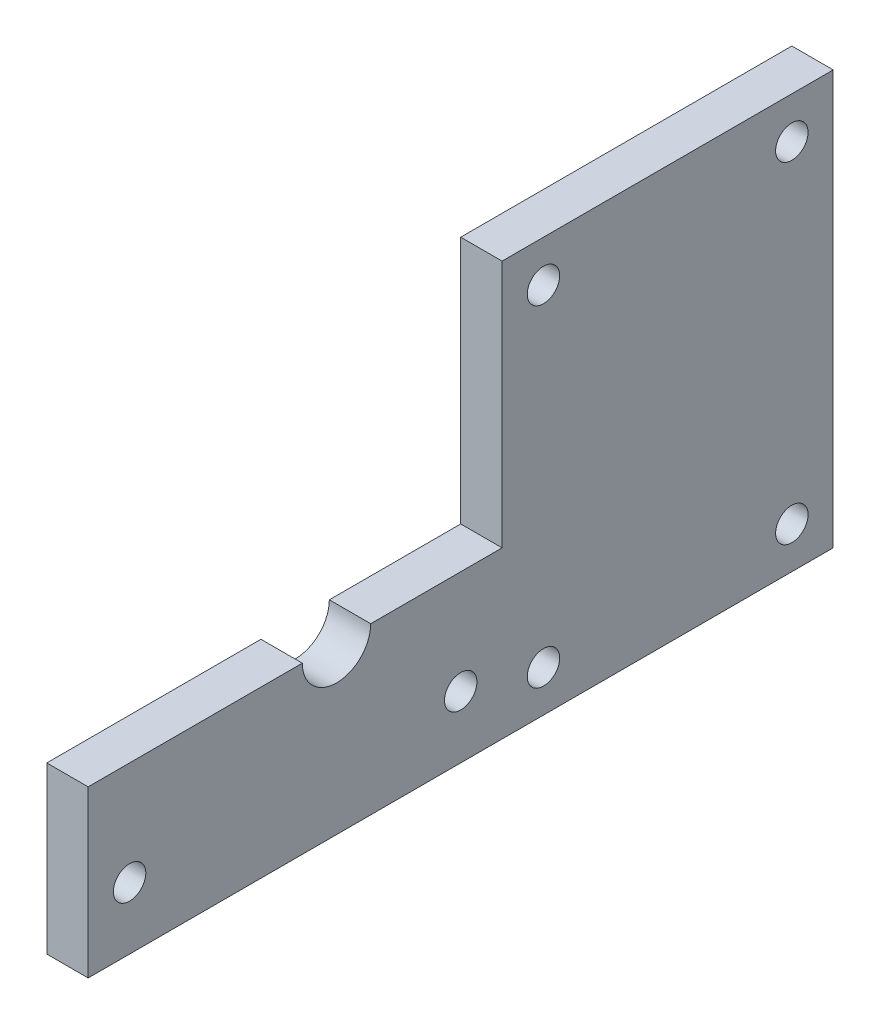
SolidWorks part; units mm, degrees
ref_plane "Front" through (0, 0, 0) normal (0, 0, 1) x (1, 0, 0)
ref_plane "Top" through (0, 0, 0) normal (0, 1, 0) x (1, 0, 0)
ref_plane "Right" through (0, 0, 0) normal (1, 0, 0) x (0, 0, -1)
sketch "Sketch1" plane through (0, 0, 0) normal (1, 0, 0) x (0, 0, -1)
  line L0 (-50.8, -6.35) -> (12.7, -6.35)
  line L1 (-50.8, -31.75) -> (63.5, -31.75)
  line L2 (-50.8, -31.75) -> (-50.8, -6.35)
  line L3 (12.7, 31.75) -> (63.5, 31.75)
  line L4 (63.5, -31.75) -> (63.5, 31.75)
  line L7 (12.7, -6.35) -> (12.7, 31.75)
  point P0 (0, 0)
  dimension "D1" = 25.4
  dimension "D2" = 50.8
  dimension "D3" = 63.5
  dimension "D4" = 31.75
  dimension "D5" = 63.5
  dimension "D6" = 63.5
extrude "Boss-Extrude1" add sketch "Sketch1" along normal blind 6.35
hole_wizard "#9 (0.196) Diameter Hole1" positions "Sketch3" profile "Sketch2" hole size "#9" standard "ANSI Inch"
sketch "Sketch3" plane through (0, 0, 0) normal (-1, 0, 0) x (0, 0, 1)
  line L0 (50.8, -31.75) -> (-63.5, -31.75) construction
  line L1 (50.8, -6.35) -> (50.8, -31.75) construction
  point P0 (44.45, -22.225)
  point P2 (-6.35, -22.225)
  dimension "D1" = 9.525
  dimension "D2" = 0
  dimension "D3" = 50.8
  dimension "D4" = 6.35
sketch "Sketch2" plane through (0, -22.225, 44.45) normal (0, 1, 0) x (0, 0, 1)
  line L0 (0, 0) -> (0, 71.5997)
  line L1 (0, 71.5997) -> (2.4892, 70.104)
  line L2 (2.4892, 70.104) -> (2.4892, 0)
  line L5 (2.4892, 0) -> (0, 0)
  line L10 (0, 71.5997) -> (-2.4892, 70.104) construction
  line L11 (0, -6.35) -> (0, 107.95) construction
  dimension "Hole Dia." = 4.9784
  dimension "Hole Depth" = 70.104
  dimension "Drill Angle" = 118
hole_wizard "#9 (0.196) Diameter Hole2" positions "Sketch5" profile "Sketch4" hole size "#9" standard "ANSI Inch"
sketch "Sketch5" plane through (0, 0, 0) normal (-1, 0, 0) x (0, 0, 1)
  line L0 (50.8, -31.75) -> (-63.5, -31.75) construction
  line L1 (-63.5, -31.75) -> (-63.5, 31.75) construction
  point P0 (-57.15, -25.4)
  point P2 (-19.05, -25.4)
  point P4 (-19.05, 25.4)
  point P6 (-57.15, 25.4)
  dimension "D1" = 6.35
  dimension "D2" = 6.35
  dimension "D3" = 0
  dimension "D4" = 50.8
  dimension "D5" = 38.1
  dimension "D6" = 50.8
  dimension "D7" = 38.1
  dimension "D8" = 0
sketch "Sketch4" plane through (0, -25.4, -57.15) normal (0, 1, 0) x (0, 0, 1)
  line L0 (0, 0) -> (0, 71.5997)
  line L1 (0, 71.5997) -> (2.4892, 70.104)
  line L2 (2.4892, 70.104) -> (2.4892, 0)
  line L5 (2.4892, 0) -> (0, 0)
  line L10 (0, 71.5997) -> (-2.4892, 70.104) construction
  line L11 (0, -6.35) -> (0, 107.95) construction
  dimension "Hole Dia." = 4.9784
  dimension "Hole Depth" = 70.104
  dimension "Drill Angle" = 118
hole_wizard "Z (0.413) Diameter Hole1" positions "Sketch7" profile "Sketch6" hole size "Z" standard "ANSI Inch"
sketch "Sketch7" plane through (0, 0, 0) normal (-1, 0, 0) x (0, 0, 1)
  line L0 (50.8, -31.75) -> (-63.5, -31.75) construction
  circle A0 centre (-6.35, -22.225) radius 2.4892 construction
  point P0 (12.7, -6.35)
  dimension "D2" = 19.05
  dimension "D1" = 25.4
sketch "Sketch6" plane through (0, -6.35, 12.7) normal (0, 1, 0) x (0, 0, 1)
  line L0 (0, 0) -> (0, 73.2556)
  line L1 (0, 73.2556) -> (5.2451, 70.104)
  line L2 (5.2451, 70.104) -> (5.2451, 0)
  line L5 (5.2451, 0) -> (0, 0)
  line L10 (0, 73.2556) -> (-5.2451, 70.104) construction
  line L11 (0, -6.35) -> (0, 107.95) construction
  dimension "Hole Dia." = 10.4902
  dimension "Hole Depth" = 70.104
  dimension "Drill Angle" = 118
